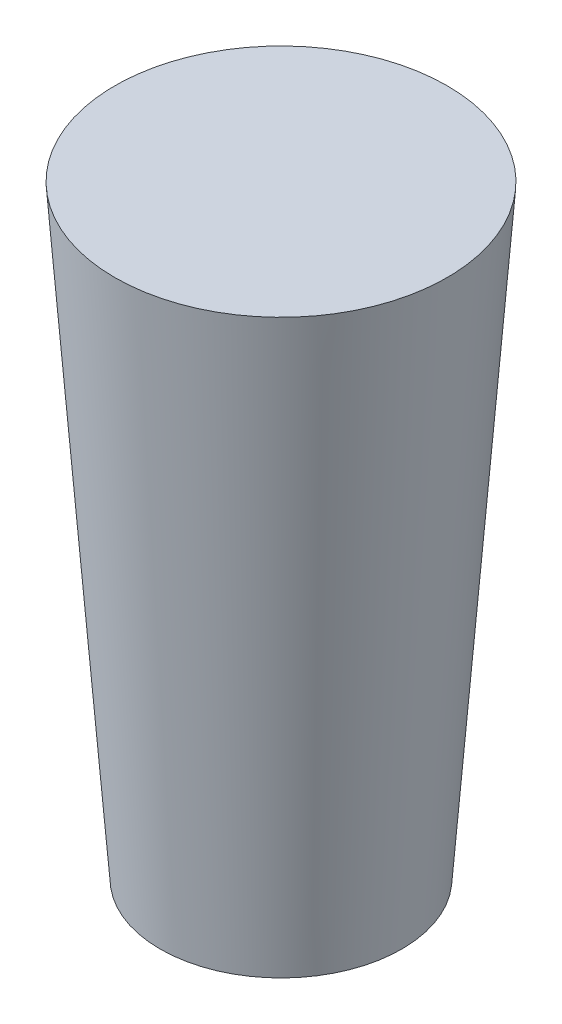
SolidWorks part; units mm, degrees
ref_plane "Front Plane" through (0, 0, 0) normal (0, 0, 1) x (1, 0, 0)
ref_plane "Top Plane" through (0, 0, 0) normal (0, 1, 0) x (1, 0, 0)
ref_plane "Right Plane" through (0, 0, 0) normal (1, 0, 0) x (0, 0, -1)
sketch "Sketch1" plane through (0, 0, 0) normal (0, 0, 1) x (1, 0, 0)
  line L0 (-0.7564, 14.9554) -> (4.7436, 14.9554)
  line L1 (4.7436, 14.9554) -> (3.2436, -5.0446)
  line L2 (3.2436, -5.0446) -> (-0.7564, -5.0446)
  line L3 (-0.7564, -5.0446) -> (-0.7564, 14.9554)
  line L4 (-0.7564, 26.8304) -> (-0.7564, -33.3482) construction
  line L5 (4.2436, 26.8304) -> (4.2436, -30.4911) construction
  dimension "D1" = 20
  dimension "D2" = 4
  dimension "D3" = 5.5
  dimension "D4" = 5
revolve "Revolve1" add sketch "Sketch1" angle 360 about L4
